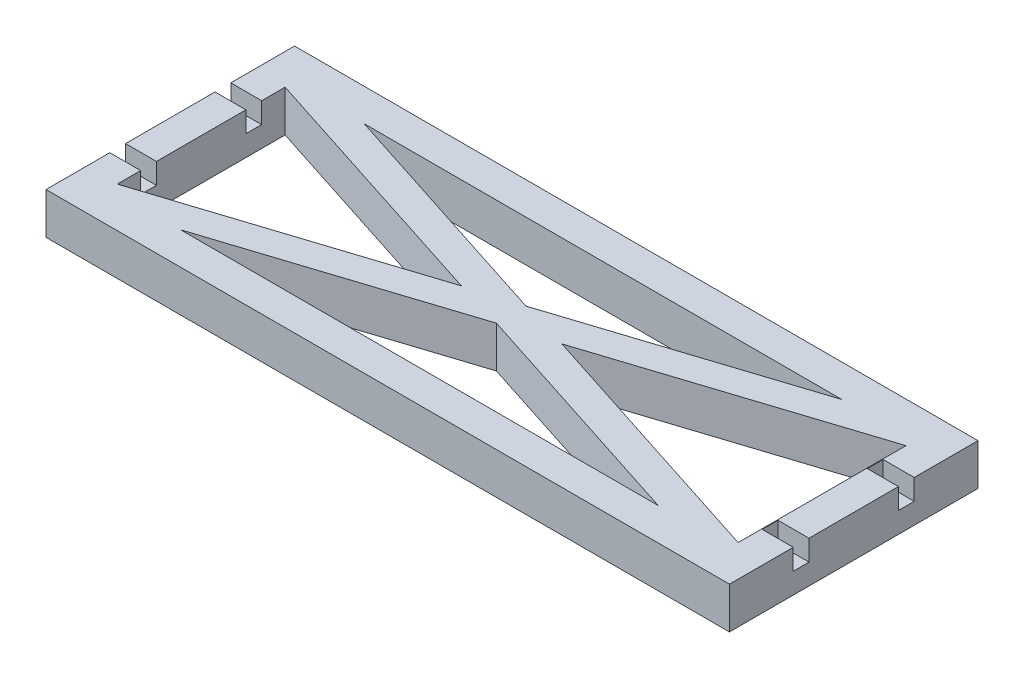
SolidWorks part; units mm, degrees
ref_plane "Front Plane" through (0, 0, 0) normal (0, 0, 1) x (1, 0, 0)
ref_plane "Top Plane" through (0, 0, 0) normal (0, 1, 0) x (1, 0, 0)
ref_plane "Right Plane" through (0, 0, 0) normal (1, 0, 0) x (0, 0, -1)
sketch "Sketch1" plane through (0, 0, 0) normal (0, 1, 0) x (1, 0, 0)
  line L5 (82.5, -30) -> (-82.5, 30) construction
  line L6 (82.5, 30) -> (-82.5, -30) construction
  line L62 (-82.5, 30) -> (-82.5, -30)
  line L63 (-82.5, -30) -> (82.5, -30)
  line L64 (82.5, -30) -> (82.5, 30)
  line L65 (82.5, 30) -> (-82.5, 30)
  line L76 (-82.5, 0) -> (82.5, 0) construction
  line L89 (-75.04, 20.2624) -> (-75.04, -20.2624)
  line L90 (-75.04, -20.2624) -> (-12.2265, 0)
  line L91 (-75.04, 20.2624) -> (-12.2265, 0)
  line L92 (57.4605, 22.1658) -> (-57.8346, 22.1658)
  line L93 (-57.8346, 22.1658) -> (-0.1871, 3.5699)
  line L94 (-0.1871, 3.5699) -> (57.4605, 22.1658)
  line L95 (74.8529, 20.2624) -> (74.8529, -20.2624)
  line L96 (74.8529, -20.2624) -> (12.0394, 0)
  line L97 (74.8529, 20.2624) -> (12.0394, 0)
  line L98 (-57.8346, -22.1658) -> (-0.1871, -3.5699)
  line L99 (-0.1871, -3.5699) -> (57.4605, -22.1658)
  line L100 (-57.8346, -22.1658) -> (57.4605, -22.1658)
  point P0 (0, 0)
  point P6 (-72.5, 16.7742)
  point P10 (-20.5, 0)
  point P16 (72.3129, 16.7742)
  point P20 (-0.1871, 6.2387)
  point P21 (20.3129, 0)
  point P22 (0, -6.6129)
  point P26 (-41.6871, 19.6258)
  point P27 (-72.5, -16.7742)
  point P30 (41.3129, 19.6258)
  dimension "D1" = 60
  dimension "D2" = 165
extrude "Boss-Extrude1" add sketch "Sketch1" along normal blind 10
sketch "Sketch2" plane through (-82.5, 0, 0) normal (-1, 0, 0) x (0, 0, 1)
  line L1 (-30, 10) -> (30, 10) construction
  line L3 (0, 10) -> (0, -1.6306) construction
  line L6 (-14.605, 10) -> (-10.795, 10)
  line L10 (14.605, 10) -> (10.795, 10)
  line L18 (-14.605, 10) -> (-14.605, 5)
  line L19 (-10.795, 5) -> (-10.795, 10)
  line L20 (-30, 0) -> (30, 0) construction
  line L22 (10.795, 10) -> (10.795, 5)
  line L24 (14.605, 10) -> (14.605, 5)
  line L26 (-10.795, 5) -> (-14.605, 5)
  line L27 (14.605, 5) -> (10.795, 5)
  point P8 (0, 2.5)
  point P25 (-12.7, 5)
  point P28 (12.7, 5)
  dimension "D1" = 5
  dimension "D2" = 3.81
  dimension "D3" = 5
  dimension "D4" = 21.59
extrude "Cut-Extrude1" cut sketch "Sketch2" against normal blind 7.5
sketch "Sketch3" plane through (0, 10, 0) normal (0, 1, 0) x (1, 0, 0)
  line L0 (0, 0) -> (0, 30) construction
  line L1 (82.5, 30) -> (-82.5, 30) construction
mirror "Mirror1" about plane through (0, 0, 0) normal (1, 0, 0) of "Cut-Extrude1"
